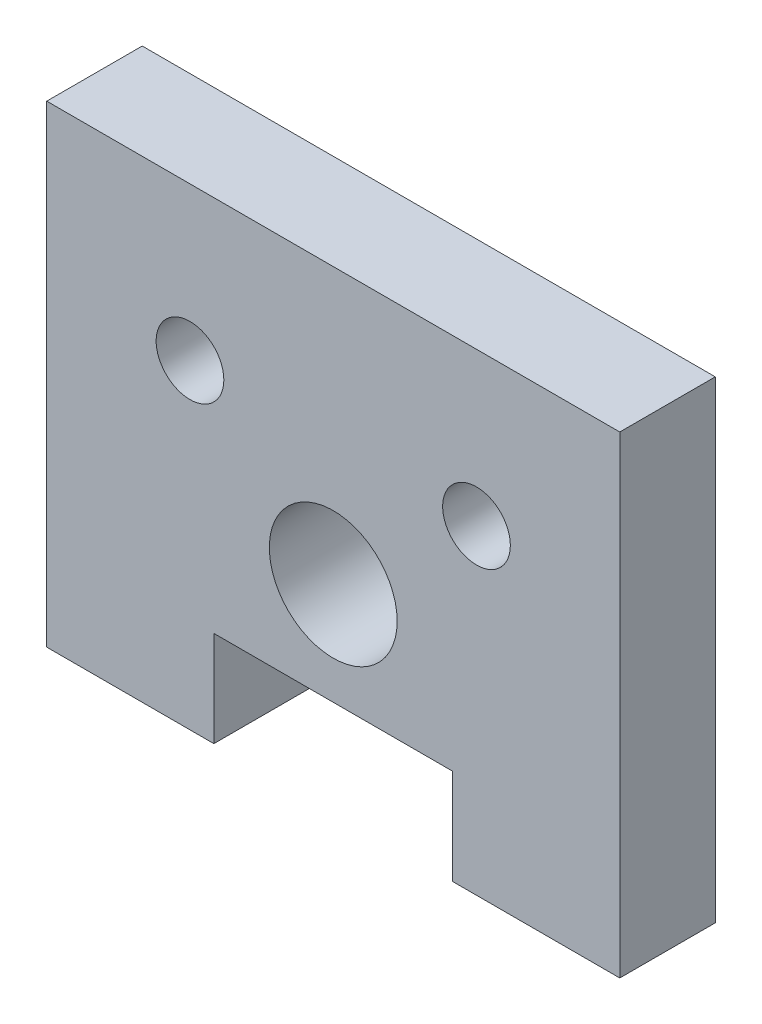
SolidWorks part; units mm, degrees
material "Acrylic (Medium-high impact)"
ref_plane "Front Plane" through (0, 0, 0) normal (0, 0, 1) x (1, 0, 0)
ref_plane "Top Plane" through (0, 0, 0) normal (0, 1, 0) x (1, 0, 0)
ref_plane "Right Plane" through (0, 0, 0) normal (1, 0, 0) x (0, 0, -1)
sketch "Sketch1" plane through (0, 0, 0) normal (0, 0, 1) x (1, 0, 0)
  line L0 (-15.875, -34.544) -> (-15.875, -21.844)
  line L1 (38.1, -34.544) -> (15.875, -34.544)
  line L2 (38.1, -34.544) -> (38.1, 34.544)
  line L4 (-38.1, -34.544) -> (-38.1, 34.544)
  line L5 (-15.875, -21.844) -> (15.875, -21.844)
  line L6 (15.875, -21.844) -> (15.875, -34.544)
  line L7 (-15.875, -34.544) -> (-38.1, -34.544)
  line L8 (0, -21.844) -> (0, -16.764)
  line L9 (-19.05, 28.3364) -> (-38.1, 28.3364)
  line L10 (-19.05, 28.3364) -> (38.1, 28.3364)
  circle A3 centre (0, -8.264) radius 8.5
  circle A4 centre (-19.05, 7.992) radius 4.5
  circle A5 centre (19.05, 7.992) radius 4.5
  point P0 (0, 0)
  point P6 (-38.1, 0)
  point P18 (0, -21.844)
  dimension "D3" = 17
  dimension "D5" = 9
  dimension "D8" = 31.75
  dimension "D9" = 12.7
  dimension "D10" = 5.08
  dimension "D4" = 16.256
  dimension "D6" = 19.05
  dimension "D7" = 19.05
  dimension "D2" = 76.2
extrude "Boss-Extrude2" add sketch "Sketch1" along normal blind 12.7
equation "\"D7@Sketch1\"=\"D6@Sketch1\""
